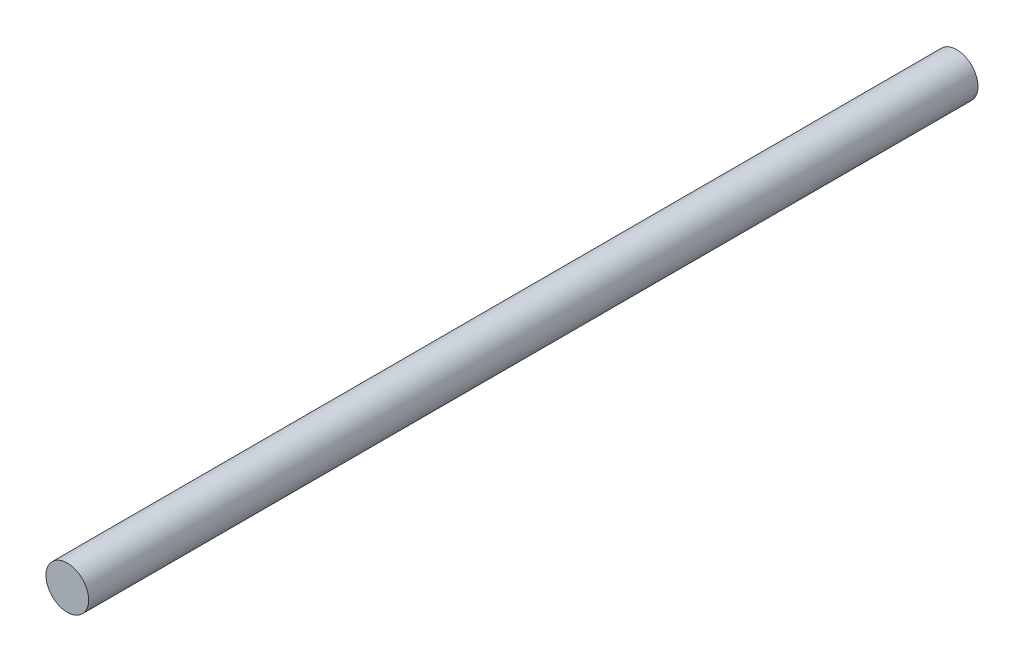
SolidWorks part; units mm, degrees
ref_plane "Front Plane" through (0, 0, 0) normal (0, 0, 1) x (1, 0, 0)
ref_plane "Top Plane" through (0, 0, 0) normal (0, 1, 0) x (1, 0, 0)
ref_plane "Right Plane" through (0, 0, 0) normal (1, 0, 0) x (0, 0, -1)
sketch "Sketch1" plane through (0, 0, 0) normal (0, 0, 1) x (1, 0, 0)
  circle A0 centre (0, 0) radius 6
  dimension "D1" = 12
extrude "Boss-Extrude1" add sketch "Sketch1" along normal blind 250
